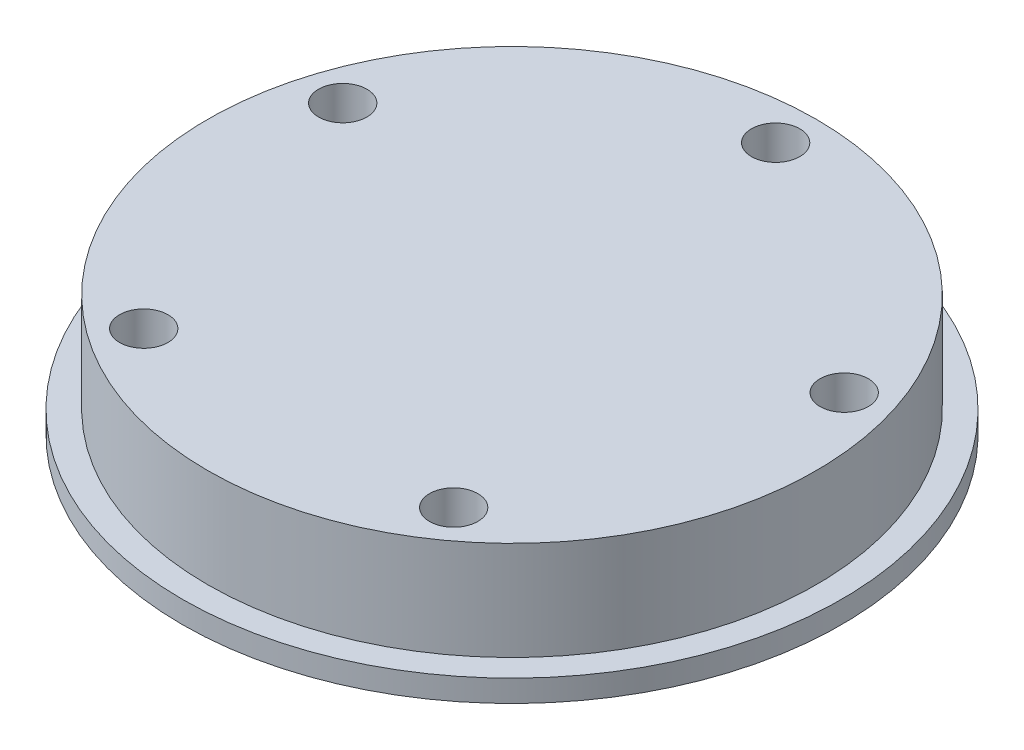
SolidWorks part; units mm, degrees
other "Markup1"
sketch "Sketch12" plane through (-30, 16, 30) normal (-0.4004, 0.8133, 0.4222) x (0.8959, 0.2506, 0.3669)
other "Markup2"
sketch "Sketch13" plane through (-30, 16, 30) normal (-0.1159, 0.8028, 0.5849) x (0.7979, -0.2754, 0.5361)
ref_plane "Front Plane" through (0, 0, 0) normal (0, 0, 1) x (1, 0, 0)
ref_plane "Top Plane" through (0, 0, 0) normal (0, 1, 0) x (1, 0, 0)
ref_plane "Right Plane" through (0, 0, 0) normal (1, 0, 0) x (0, 0, -1)
sketch "Sketch3" plane through (0, 0, 0) normal (0, 1, 0) x (1, 0, 0)
  circle A0 centre (0, 0) radius 27.7
  dimension "D1" = 55.4
extrude "Boss-Extrude2" add sketch "Sketch3" along normal blind 11
sketch "Sketch4" plane through (0, 0, 0) normal (0, 1, 0) x (1, 0, 0)
  circle A0 centre (0, 0) radius 30
  dimension "D1" = 60
extrude "Boss-Extrude3" add sketch "Sketch4" along normal blind 2
sketch "Sketch5" plane through (0, 11, 0) normal (0, 1, 0) x (1, 0, 0)
  circle A0 centre (0, 0) radius 24 construction
  circle A1 centre (0, 24) radius 2.2
  circle A2 centre (22.8254, 7.4164) radius 2.2
  circle A3 centre (14.1068, -19.4164) radius 2.2
  circle A4 centre (-14.1068, -19.4164) radius 2.2
  circle A5 centre (-22.8254, 7.4164) radius 2.2
  point P15 (0, 0)
  dimension "D1" = 48
  dimension "D2" = 4.4
  dimension "D4" = 24
  dimension "D3" = 5
extrude "Cut-Extrude1" cut sketch "Sketch5" against normal through all
